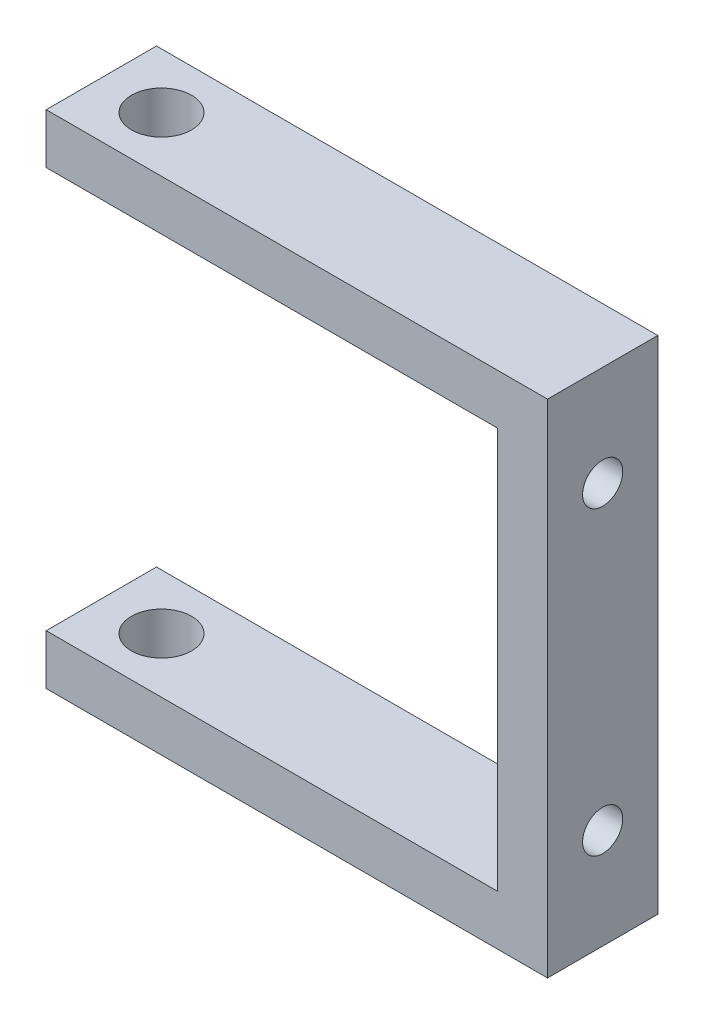
SolidWorks part; units mm, degrees
ref_plane "Front Plane" through (0, 0, 0) normal (0, 0, 1) x (1, 0, 0)
ref_plane "Top Plane" through (0, 0, 0) normal (0, 1, 0) x (1, 0, 0)
ref_plane "Right Plane" through (0, 0, 0) normal (1, 0, 0) x (0, 0, -1)
sketch "Sketch1" plane through (0, 0, 0) normal (0, 0, 1) x (1, 0, 0)
  line L0 (0, 50) -> (50, 50)
  line L1 (50, 50) -> (50, 0)
  line L2 (50, 0) -> (0, 0)
  line L3 (0, 0) -> (0, 5)
  line L4 (0, 5) -> (45, 5)
  line L5 (45, 5) -> (45, 45)
  line L6 (45, 45) -> (0, 45)
  line L7 (0, 45) -> (0, 50)
  line L8 (0, 5) -> (0, 45) construction
  dimension "D1" = 5
  dimension "D2" = 5
  dimension "D3" = 50
  dimension "D4" = 45
  dimension "D5" = 5
extrude "Boss-Extrude1" add sketch "Sketch1" along normal blind 11
sketch "Sketch2" plane through (0, 50, 0) normal (0, 1, 0) x (1, 0, 0)
  line L0 (0, -5.5) -> (50, -5.5) construction
  line L1 (0, -11) -> (0, 0) construction
  line L2 (50, -11) -> (50, 0) construction
  line L3 (6, -5.5) -> (6, 0) construction
  line L4 (50, 0) -> (0, 0) construction
  circle A0 centre (6, -5.5) radius 3
  point P8 (6.5252, -18.0503)
  dimension "D1" = 6
  dimension "D2" = 6
extrude "Cut-Extrude1" cut sketch "Sketch2" against normal blind 60
sketch "Sketch4" plane through (45, 0, 0) normal (-1, 0, 0) x (0, 0, 1)
  line L0 (5.5, 45) -> (5.5, 5) construction
  line L1 (11, 45) -> (0, 45) construction
  line L2 (11, 5) -> (0, 5) construction
  circle A0 centre (5.5, 40) radius 2
  circle A1 centre (5.5, 10) radius 2
  point P10 (17.7961, 37.9473)
  point P11 (0, 0)
  point P12 (0, 0)
  point P13 (0, 0)
  dimension "D3" = 4
  dimension "D4" = 4
  dimension "D1" = 10
  dimension "D2" = 10
extrude "Cut-Extrude2" cut sketch "Sketch4" against normal blind 11
